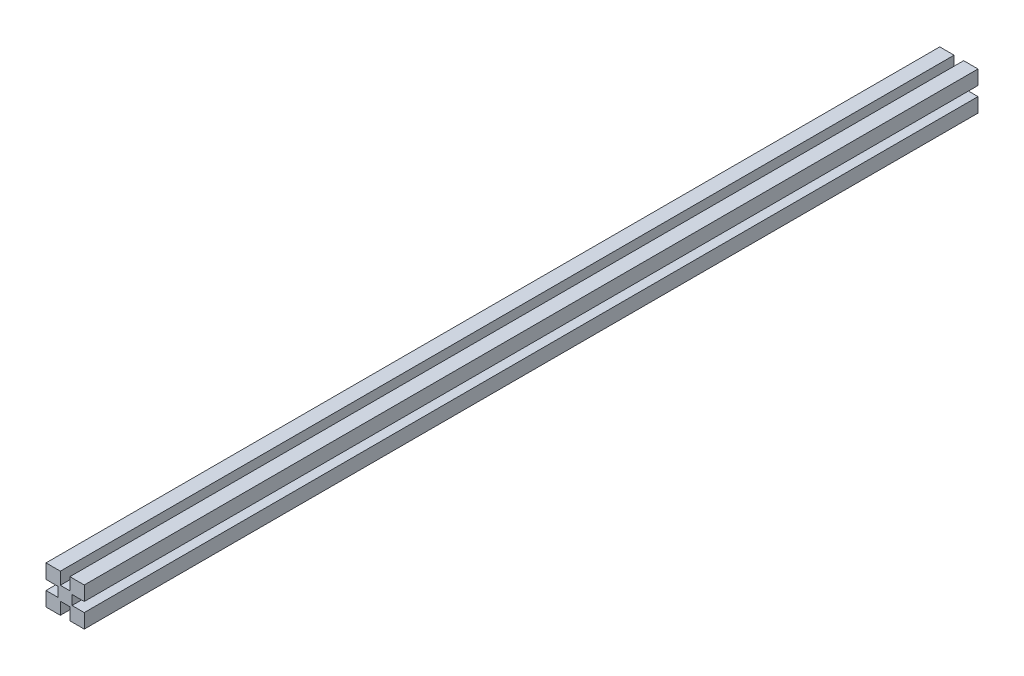
SolidWorks part; units mm, degrees
ref_plane "Front Plane" through (0, 0, 0) normal (0, 0, 1) x (1, 0, 0)
ref_plane "Top Plane" through (0, 0, 0) normal (0, 1, 0) x (1, 0, 0)
ref_plane "Right Plane" through (0, 0, 0) normal (1, 0, 0) x (0, 0, -1)
sketch "Sketch1" plane through (0, 0, 0) normal (0, 0, 1) x (1, 0, 0)
  line L0 (-12.7, 12.7) -> (-12.7, 3.175)
  line L5 (-12.7, 3.175) -> (-4.572, 3.175)
  line L6 (-4.572, 3.175) -> (-4.572, -3.175)
  line L7 (-4.572, -3.175) -> (-12.7, -3.175)
  line L8 (-12.7, -3.175) -> (-12.7, -12.7)
  line L9 (-12.7, -12.7) -> (-3.175, -12.7)
  line L10 (-3.175, -12.7) -> (-3.175, -4.572)
  line L11 (-3.175, -4.572) -> (3.175, -4.572)
  line L12 (3.175, -4.572) -> (3.175, -12.7)
  line L13 (3.175, -12.7) -> (12.7, -12.7)
  line L14 (12.7, -12.7) -> (12.7, -3.175)
  line L15 (12.7, -3.175) -> (4.572, -3.175)
  line L16 (4.572, -3.175) -> (4.572, 3.175)
  line L17 (4.572, 3.175) -> (12.7, 3.175)
  line L18 (12.7, 3.175) -> (12.7, 12.7)
  line L20 (-12.7, 12.7) -> (-3.175, 12.7)
  line L21 (-3.175, 12.7) -> (-3.175, 4.572)
  line L22 (-3.175, 4.572) -> (3.175, 4.572)
  line L23 (3.175, 4.572) -> (3.175, 12.7)
  line L24 (3.175, 12.7) -> (12.7, 12.7)
  point P0 (0, 0)
  point P19 (4.572, 0)
  point P23 (0, -4.572)
  dimension "D1" = 25.4
  dimension "D2" = 25.4
  dimension "D3" = 9.144
  dimension "D4" = 9.144
  dimension "D5" = 6.35
  dimension "D6" = 6.35
  dimension "D7" = 9.525
  dimension "D8" = 9.525
  dimension "D9" = 8.128
  dimension "D10" = 8.128
extrude "Boss-Extrude1" add sketch "Sketch1" along normal blind 593.344
